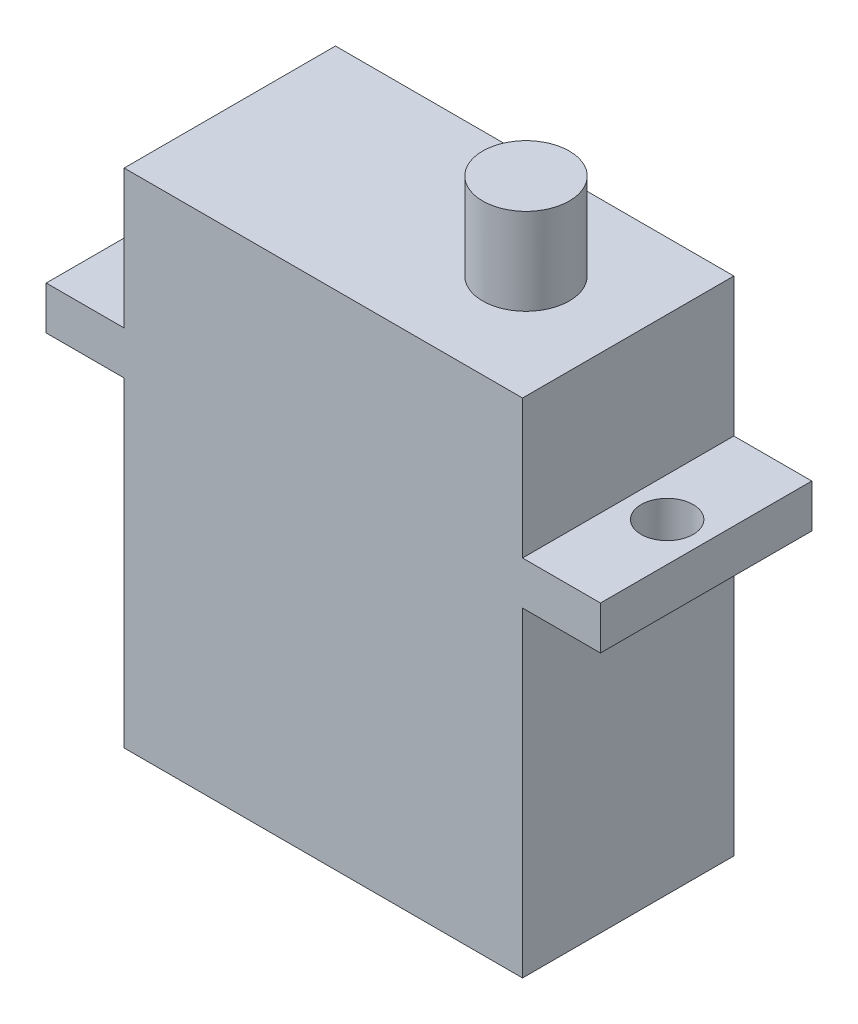
SolidWorks part; units mm, degrees
ref_plane "Спереди" through (0, 0, 0) normal (0, 0, 1) x (1, 0, 0)
ref_plane "Сверху" through (0, 0, 0) normal (0, 1, 0) x (1, 0, 0)
ref_plane "Справа" through (0, 0, 0) normal (1, 0, 0) x (0, 0, -1)
other "Configuration Table"
sketch "Эскиз1" plane through (0, 0, 0) normal (0, 1, 0) x (1, 0, 0)
  line L1 (-11.5, -6.1) -> (11.5, -6.1)
  line L2 (-11.5, -6.1) -> (-11.5, 6.1)
  line L3 (-11.5, 6.1) -> (11.5, 6.1)
  line L4 (11.5, -6.1) -> (11.5, 6.1)
  line L5 (-11.5, -6.1) -> (11.5, 6.1) construction
  line L6 (-11.5, 6.1) -> (11.5, -6.1) construction
  point P0 (0, 0)
  dimension "D1" = 12.2
  dimension "D2" = 23
extrude "Бобышка-Вытянуть1" add sketch "Эскиз1" along normal blind 29
sketch "Эскиз2" plane through (0, 0, -6.1) normal (0, 0, -1) x (-1, 0, 0)
  line L5 (-11.5, 29) -> (11.5, 29) construction
  line L6 (-16, 18.5) -> (16, 18.5)
  line L8 (-16, 18.5) -> (-16, 21)
  line L9 (-16, 21) -> (16, 21)
  line L10 (16, 18.5) -> (16, 21)
  line L11 (-16, 18.5) -> (16, 21) construction
  line L12 (-16, 21) -> (16, 18.5) construction
  point P0 (0, 19.75)
  dimension "D1" = 2.5
  dimension "D2" = 32
  dimension "D3" = 0
  dimension "D4" = 8
extrude "Бобышка-Вытянуть2" add sketch "Эскиз2" against normal up to surface (12.2 mm away) up to face at (0, 14.5, 6.1)
sketch "Эскиз3" plane through (0, 21, 0) normal (0, 1, 0) x (1, 0, 0)
  line L0 (0, -4.3302) -> (0, 4.3302) construction
  circle A0 centre (13.75, 0) radius 1.5
  circle A1 centre (-13.75, 0) radius 1.5
  point P6 (0, 0)
  dimension "D1" = 3
extrude "Вырез-Вытянуть1" cut sketch "Эскиз3" against normal blind 6 contours A0 | A1
sketch "Эскиз4" plane through (0, 29, 0) normal (0, 1, 0) x (1, 0, 0)
  line L0 (11.5, -6.1) -> (11.5, 6.1) construction
  line L1 (11.5, 6.1) -> (-11.5, 6.1) construction
  circle A0 centre (5.5, 0.1) radius 2.5
  point P6 (6.7085, -0.5878)
  dimension "D3" = 5
  dimension "D1" = 6
  dimension "D2" = 6
extrude "Бобышка-Вытянуть3" add sketch "Эскиз4" along normal blind 5
